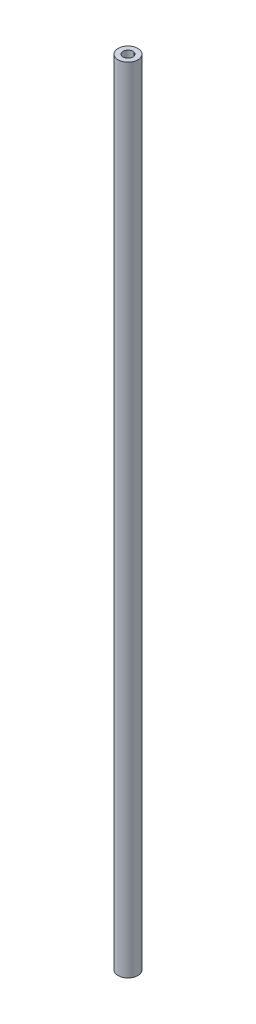
SolidWorks part; units mm, degrees
material "PA Type 6"
ref_plane "Front Plane" through (0, 0, 0) normal (0, 0, 1) x (1, 0, 0)
ref_plane "Top Plane" through (0, 0, 0) normal (0, 1, 0) x (1, 0, 0)
ref_plane "Right Plane" through (0, 0, 0) normal (1, 0, 0) x (0, 0, -1)
sketch "Sketch1" plane through (0, 0, 0) normal (0, 1, 0) x (1, 0, 0)
  circle A0 centre (0, 0) radius 1.27
  circle A1 centre (0, 0) radius 0.635
  dimension "D1" = 1.27
  dimension "D2" = 2.54
extrude "Boss-Extrude1" add sketch "Sketch1" along normal blind 101.6
